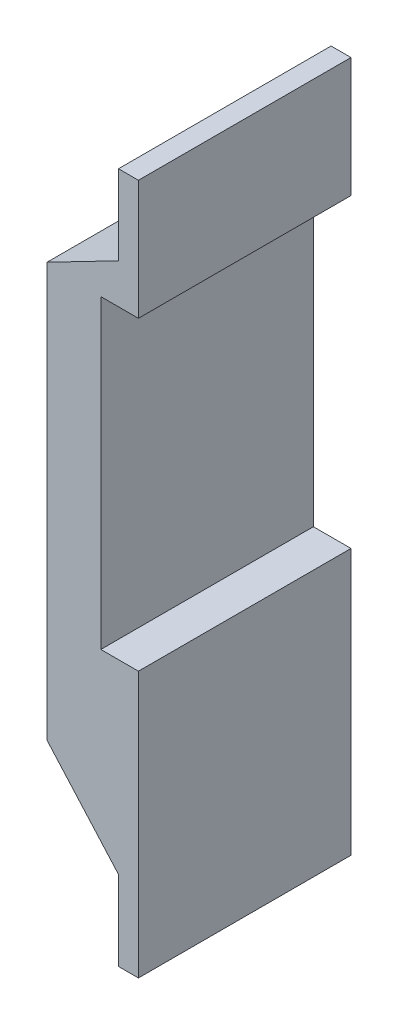
SolidWorks part; units mm, degrees
ref_plane "Front Plane" through (0, 0, 0) normal (0, 0, 1) x (1, 0, 0)
ref_plane "Top Plane" through (0, 0, 0) normal (0, 1, 0) x (1, 0, 0)
ref_plane "Right Plane" through (0, 0, 0) normal (1, 0, 0) x (0, 0, -1)
sketch "Sketch1" plane through (0, 0, 0) normal (0, 0, 1) x (1, 0, 0)
  line L2 (-5.3815, 13.8866) -> (-5.3815, -17.2673)
  line L3 (-5.3815, -17.2673) -> (0, -23.3273)
  line L4 (0, -23.3273) -> (0, -29.3273)
  line L5 (0, 22.6727) -> (1.5, 22.6727)
  line L6 (1.5, 22.6727) -> (1.5, 13.6727)
  line L9 (-1.33, -9.3273) -> (1.5, -9.3273)
  line L11 (1.5, -29.3273) -> (0, -29.3273)
  line L12 (1.5, 13.6727) -> (-1.33, 13.6727)
  line L14 (-1.33, 13.6727) -> (-1.33, -9.3273)
  line L15 (1.5, -9.3273) -> (1.5, -29.3273)
  line L16 (0, 22.6727) -> (0, 16.6727)
  line L17 (0, 16.6727) -> (-5.3815, 13.8866)
  dimension "D1" = 9
  dimension "D2" = 23
  dimension "D3" = 52
  dimension "D4" = 6
  dimension "D5" = 6
  dimension "D6" = 6.06
  dimension "D7" = 1.5
  dimension "D8" = 1.5
  dimension "D9" = 2.83
  dimension "D10" = 6.06
extrude "Boss-Extrude1" add sketch "Sketch1" along normal blind 16
